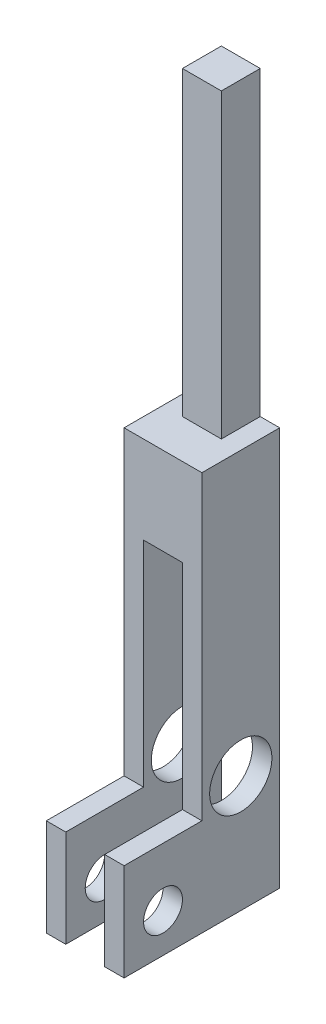
SolidWorks part; units mm, degrees
ref_plane "Front Plane" through (0, 0, 0) normal (0, 0, 1) x (1, 0, 0)
ref_plane "Top Plane" through (0, 0, 0) normal (0, 1, 0) x (1, 0, 0)
ref_plane "Right Plane" through (0, 0, 0) normal (1, 0, 0) x (0, 0, -1)
sketch "Sketch1" plane through (0, 0, 0) normal (0, 1, 0) x (1, 0, 0)
  line L1 (0, 0) -> (20, 0)
  line L2 (0, 0) -> (0, 40)
  line L3 (0, 40) -> (20, 40)
  line L4 (20, 0) -> (20, 40)
extrude "Boss-Extrude1" add sketch "Sketch1" along normal blind 180
sketch "Sketch2" plane through (0, 0, 0) normal (-1, 0, 0) x (0, 0, 1)
  line L0 (-40, 0) -> (0, 0) construction
  line L1 (0, 180) -> (0, 0) construction
  line L2 (-20, 25) -> (0, 25)
  line L3 (-20, 25) -> (-20, 180)
  line L4 (-20, 180) -> (0, 180)
  line L5 (0, 25) -> (0, 180)
  point P0 (-20, 0)
  point P1 (-10, 0)
extrude "Cut-Extrude1" cut sketch "Sketch2" against normal blind 29
sketch "Sketch3" plane through (0, 0, 0) normal (-1, 0, 0) x (0, 0, 1)
  line L0 (-20, 180) -> (-20, 25) construction
  line L1 (-20, 102.5) -> (-30, 102.5)
  line L2 (-20, 102.5) -> (-20, 180)
  line L3 (-20, 180) -> (-30, 180)
  line L4 (-30, 102.5) -> (-30, 180)
  line L5 (-40, 180) -> (-20, 180) construction
extrude "Cut-Extrude2" cut sketch "Sketch3" against normal blind 29
sketch "Sketch4" plane through (0, 0, -40) normal (0, 0, -1) x (-1, 0, 0)
  line L0 (-20, 0) -> (0, 0) construction
  line L1 (-5, 0) -> (-15, 0)
  line L2 (-5, 0) -> (-5, 80)
  line L3 (-5, 80) -> (-15, 80)
  line L4 (-15, 0) -> (-15, 80)
extrude "Cut-Extrude3" cut sketch "Sketch4" against normal blind 49
sketch "Sketch5" plane through (0, 0, -30) normal (0, 0, 1) x (1, 0, 0)
  line L0 (20, 102.5) -> (0, 102.5) construction
  line L1 (0, 180) -> (5, 180)
  line L2 (0, 180) -> (0, 102.5)
  line L3 (0, 102.5) -> (5, 102.5)
  line L4 (5, 180) -> (5, 102.5)
extrude "Cut-Extrude4" cut sketch "Sketch5" against normal blind 49
sketch "Sketch6" plane through (0, 0, -30) normal (0, 0, 1) x (1, 0, 0)
  line L0 (20, 102.5) -> (5, 102.5) construction
  line L1 (20, 180) -> (15, 180)
  line L2 (20, 180) -> (20, 102.5)
  line L3 (20, 102.5) -> (15, 102.5)
  line L4 (15, 180) -> (15, 102.5)
extrude "Cut-Extrude5" cut sketch "Sketch6" against normal blind 49
sketch "Sketch7" plane through (20, 0, 0) normal (1, 0, 0) x (0, 0, -1)
  circle A0 centre (10, 10) radius 5
extrude "Cut-Extrude6" cut sketch "Sketch7" against normal blind 49
sketch "Sketch8" plane through (20, 0, 0) normal (1, 0, 0) x (0, 0, -1)
  circle A0 centre (30, 30) radius 8
extrude "Cut-Extrude7" cut sketch "Sketch8" against normal blind 49
